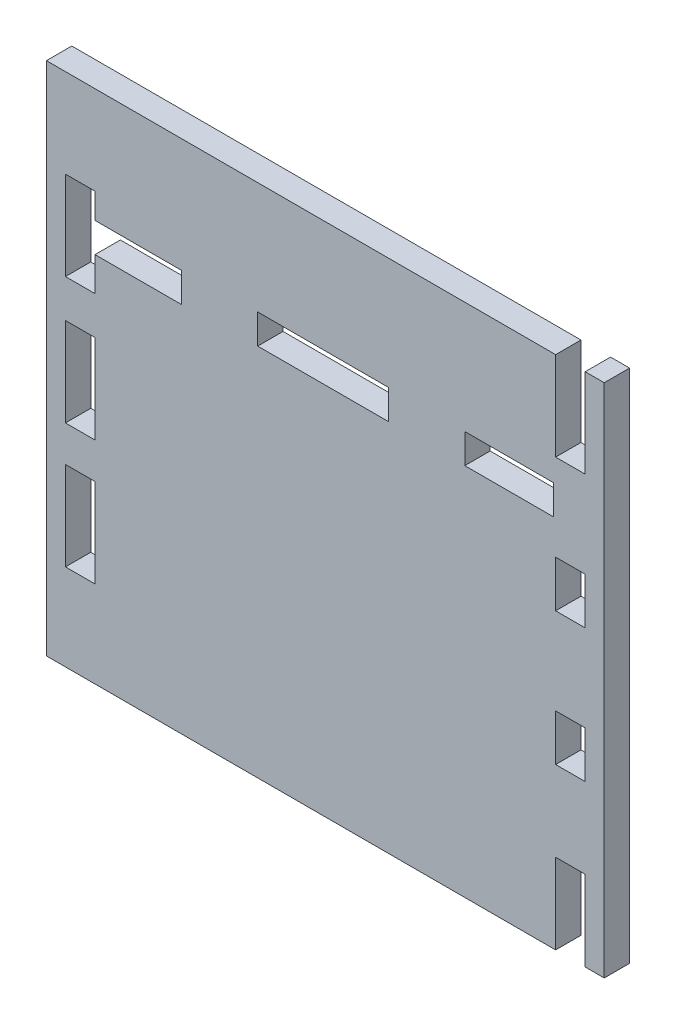
SolidWorks part; units mm, degrees
ref_plane "Спереди" through (0, 0, 0) normal (0, 0, 1) x (1, 0, 0)
ref_plane "Сверху" through (0, 0, 0) normal (0, 1, 0) x (1, 0, 0)
ref_plane "Справа" through (0, 0, 0) normal (1, 0, 0) x (0, 0, -1)
sketch "Эскиз1" plane through (0, 0, 0) normal (0, 0, 1) x (1, 0, 0)
  line L0 (-27.25, 13.25) -> (-27.25, 9.25)
  line L1 (-30.75, 19.75) -> (-27.25, 19.75)
  line L2 (-30.75, 19.75) -> (-30.75, 9.25)
  line L3 (-30.75, 9.25) -> (-27.25, 9.25)
  line L4 (-27.25, 19.75) -> (-27.25, 16.75)
  line L5 (-27.25, 16.75) -> (-17, 16.75)
  line L6 (-27.25, 13.25) -> (-17, 13.25)
  line L7 (-17, 16.75) -> (-17, 13.25)
  line L8 (-8, 17) -> (7.5, 17)
  line L9 (-8, 17) -> (-8, 13.5)
  line L10 (-8, 13.5) -> (7.5, 13.5)
  line L11 (7.5, 17) -> (7.5, 13.5)
  line L12 (16.5, 17) -> (27, 17)
  line L13 (16.5, 17) -> (16.5, 13.5)
  line L14 (16.5, 13.5) -> (27, 13.5)
  line L15 (27, 17) -> (27, 13.5)
  line L16 (30.75, -30.75) -> (33, -30.75)
  line L17 (30.75, 30.25) -> (33, 30.25)
  line L18 (27.25, 9.5) -> (30.75, 9.5)
  line L19 (27.25, 9.5) -> (27.25, 4)
  line L20 (27.25, 4) -> (30.75, 4)
  line L21 (30.75, 9.5) -> (30.75, 4)
  line L22 (27.25, -6.25) -> (30.75, -6.25)
  line L23 (27.25, -6.25) -> (27.25, -11.75)
  line L24 (27.25, -11.75) -> (30.75, -11.75)
  line L25 (30.75, -6.25) -> (30.75, -11.75)
  line L26 (-30.75, 4.75) -> (-27.25, 4.75)
  line L27 (-30.75, 4.75) -> (-30.75, -5.75)
  line L28 (-30.75, -5.75) -> (-27.25, -5.75)
  line L29 (-27.25, 4.75) -> (-27.25, -5.75)
  line L30 (-30.75, -10) -> (-27.25, -10)
  line L31 (-30.75, -10) -> (-30.75, -20.5)
  line L32 (-30.75, -20.5) -> (-27.25, -20.5)
  line L33 (-27.25, -10) -> (-27.25, -20.5)
  line L34 (-33, 30.25) -> (27.25, 30.25)
  line L35 (-33, 30.25) -> (-33, -30.75)
  line L36 (-33, -30.75) -> (27.25, -30.75)
  line L37 (27.25, 30.25) -> (27.25, 19.75)
  line L38 (27.25, 19.75) -> (30.75, 19.75)
  line L39 (30.75, 30.25) -> (30.75, 19.75)
  line L40 (27.25, -21.25) -> (30.75, -21.25)
  line L41 (27.25, -21.25) -> (27.25, -30.75)
  line L42 (33, 30.25) -> (33, -30.75)
  line L43 (30.75, -21.25) -> (30.75, -30.75)
  point P48 (-32.1071, 31.8061)
  dimension "D1" = 66
  dimension "D2" = 61
  dimension "D3" = 10.5
  dimension "D4" = 2.25
  dimension "D5" = 4.25
  dimension "D6" = 10.25
  dimension "D7" = 10.5
  dimension "D8" = 10.5
  dimension "D9" = 10.5
  dimension "D10" = 2.25
  dimension "D11" = 2.25
  dimension "D12" = 3.5
  dimension "D13" = 3.5
  dimension "D14" = 3.5
  dimension "D15" = 10.25
  dimension "D16" = 15.5
  dimension "D17" = 10.5
  dimension "D18" = 9
  dimension "D19" = 9
  dimension "D20" = 3.5
  dimension "D21" = 3.5
  dimension "D22" = 3.5
  dimension "D23" = 3
  dimension "D24" = 3.5
  dimension "D25" = 3.5
  dimension "D26" = 3.5
  dimension "D27" = 3.5
  dimension "D28" = 2.25
  dimension "D29" = 10.5
  dimension "D30" = 5.5
  dimension "D31" = 5.5
  dimension "D32" = 2.25
  dimension "D33" = 10.25
  dimension "D34" = 10.25
  dimension "D35" = 9.5
  dimension "D36" = 2.25
  dimension "D37" = 2.25
extrude "Бобышка-Вытянуть1" add sketch "Эскиз1" along normal blind 3
